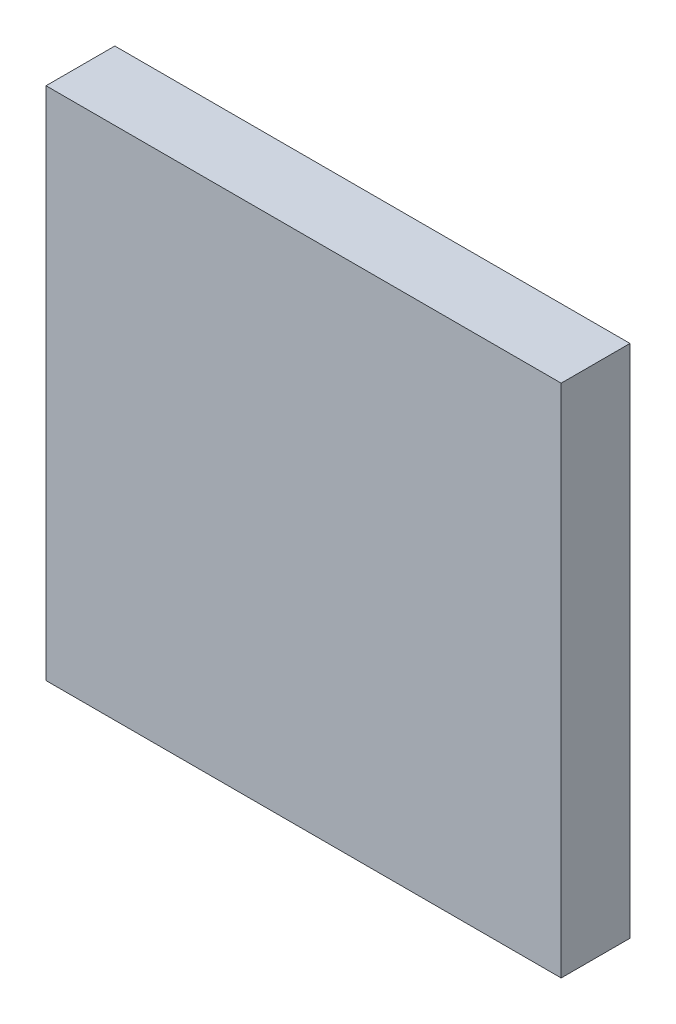
SolidWorks part; units mm, degrees
material "Polyurethane Foam Rigid"
ref_plane "Front Plane" through (0, 0, 0) normal (0, 0, 1) x (1, 0, 0)
ref_plane "Top Plane" through (0, 0, 0) normal (0, 1, 0) x (1, 0, 0)
ref_plane "Right Plane" through (0, 0, 0) normal (1, 0, 0) x (0, 0, -1)
sketch "Sketch1" plane through (0, 0, 0) normal (0, 0, 1) x (1, 0, 0)
  line L1 (112.3, -112.3) -> (-112.3, -112.3)
  line L2 (112.3, -112.3) -> (112.3, 112.3)
  line L3 (112.3, 112.3) -> (-112.3, 112.3)
  line L4 (-112.3, -112.3) -> (-112.3, 112.3)
  line L5 (112.3, -112.3) -> (-112.3, 112.3) construction
  line L6 (112.3, 112.3) -> (-112.3, -112.3) construction
  point P0 (0, 0)
  dimension "D1" = 224.6
  dimension "D2" = 224.6
extrude "Boss-Extrude1" add sketch "Sketch1" along normal blind 30
